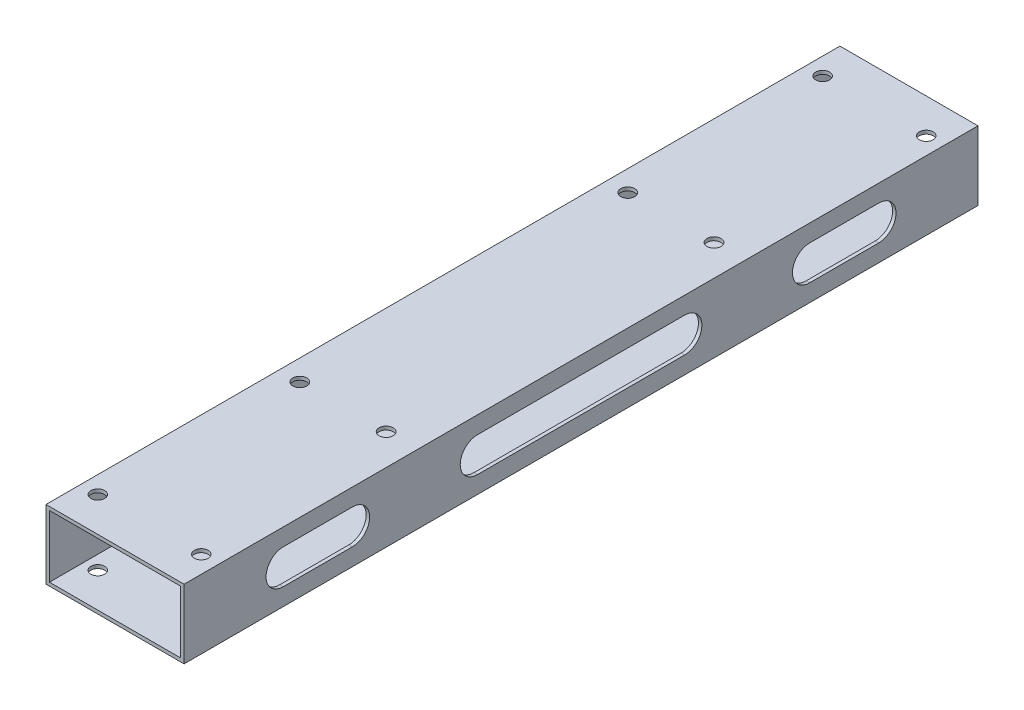
SolidWorks part; units mm, degrees
material "6063-T5"
ref_plane "前视基准面" through (0, 0, 0) normal (0, 0, 1) x (1, 0, 0)
ref_plane "上视基准面" through (0, 0, 0) normal (0, 1, 0) x (1, 0, 0)
ref_plane "右视基准面" through (0, 0, 0) normal (1, 0, 0) x (0, 0, -1)
sketch "草图1" plane through (0, 0, 0) normal (0, 0, 1) x (1, 0, 0)
  line L0 (-19, -9) -> (-19, 9)
  line L1 (-20, -10) -> (20, -10)
  line L2 (-20, -10) -> (-20, 10)
  line L3 (-20, 10) -> (20, 10)
  line L4 (20, -10) -> (20, 10)
  line L5 (0, 10) -> (0, -10) construction
  line L6 (-20, 0) -> (20, 0) construction
  line L7 (-19, 9) -> (19, 9)
  line L8 (19, -9) -> (19, 9)
  line L9 (-19, -9) -> (19, -9)
  point P0 (0, 0)
  dimension "D1" = 20
  dimension "D2" = 40
  dimension "D3" = 1
extrude "凸台-拉伸1" add sketch "草图1" along normal mid plane 230
sketch "草图2" plane through (0, 10, 0) normal (0, 1, 0) x (1, 0, 0)
  line L0 (-15, 105) -> (15, 105) construction
  line L5 (0, 105) -> (0, 0) construction
  line L6 (20, 115) -> (-20, 115) construction
  circle A0 centre (-15, 105) radius 2
  circle A1 centre (15, 105) radius 2
  point P3 (0, 105)
  dimension "D3" = 4
  dimension "D1" = 30
  dimension "D2" = 10
extrude "切除-拉伸1" cut sketch "草图2" against normal mid plane 230
mirror "镜向1" about plane through (0, 0, 0) normal (0, 0, 1) of "切除-拉伸1"
sketch "草图3" plane through (0, -10, 0) normal (0, -1, 0) x (1, 0, 0)
  circle A0 centre (-13.9757, -47.5) radius 2.025 construction
  circle A1 centre (11.0243, -47.5) radius 2.025 construction
  circle A2 centre (-13.9757, 47.5) radius 2.025 construction
  circle A3 centre (11.0243, 47.5) radius 2.025 construction
  circle A4 centre (-13.9757, -47.5) radius 2.025
  circle A5 centre (11.0243, -47.5) radius 2.025
  circle A6 centre (-13.9757, 47.5) radius 2.025
  circle A7 centre (11.0243, 47.5) radius 2.025
extrude "切除-拉伸2" cut sketch "草图3" against normal mid plane 70
sketch "草图4" plane through (20, 0, 0) normal (1, 0, 0) x (0, 0, -1)
  line L0 (-30, 0) -> (30, 0) construction
  line L1 (-30, 5) -> (30, 5)
  line L2 (-30, -5) -> (30, -5)
  arc A0 (-30, 5) -> (-30, -5) centre (-30, 0) ccw
  arc A1 (30, -5) -> (30, 5) centre (30, 0) ccw
  point P2 (0, 0)
  dimension "D1" = 5
  dimension "D2" = 60
extrude "切除-拉伸3" cut sketch "草图4" against normal mid plane 259
sketch "草图5" plane through (20, 0, 0) normal (1, 0, 0) x (0, 0, -1)
  line L0 (-86.25, 0) -> (-66.25, 0) construction
  line L1 (-86.25, 5) -> (-66.25, 5)
  line L2 (-86.25, -5) -> (-66.25, -5)
  line L3 (-45.475, 10) -> (-49.525, 10) construction
  line L4 (-103, 10) -> (-107, 10) construction
  line L5 (-45.475, 10) -> (-49.525, 10) construction
  line L6 (-103, 10) -> (-107, 10) construction
  line L7 (-105, 10) -> (-105, -10) construction
  line L8 (-115, -10) -> (115, -10) construction
  line L9 (-47.5, 10) -> (-47.5, -10) construction
  line L10 (-105, 0) -> (-47.5, 0) construction
  arc A0 (-86.25, 5) -> (-86.25, -5) centre (-86.25, 0) ccw
  arc A1 (-66.25, -5) -> (-66.25, 5) centre (-66.25, 0) ccw
  arc A2 (-30, 5) -> (-30, -5) centre (-30, 0) ccw construction
  point P2 (-76.25, 0)
  point P23 (0, 0)
  dimension "D1" = 20
extrude "切除-拉伸4" cut sketch "草图5" against normal mid plane 259
mirror "镜向2" about plane through (0, 0, 0) normal (0, 0, 1) of "切除-拉伸4"
